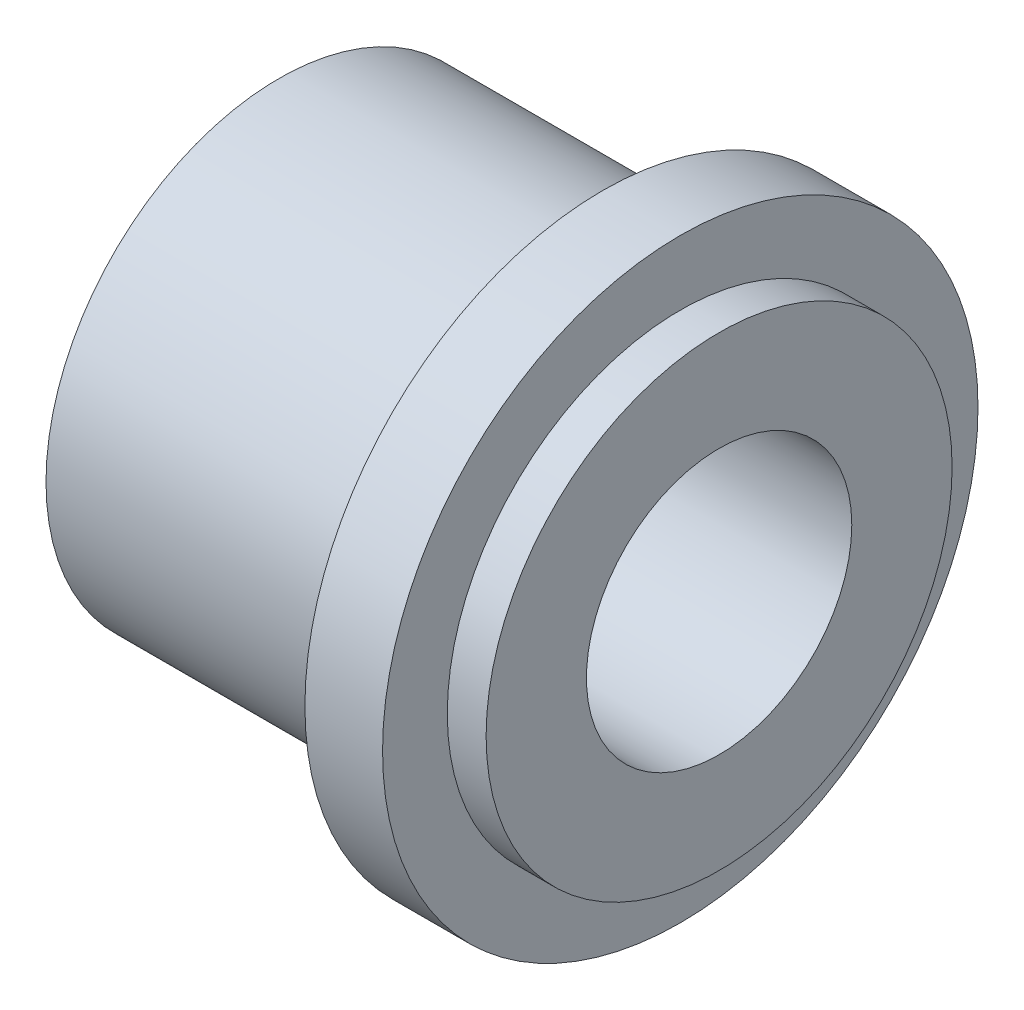
SolidWorks part; units mm, degrees
ref_plane "前视基准面" through (0, 0, 0) normal (0, 0, 1) x (1, 0, 0)
ref_plane "上视基准面" through (0, 0, 0) normal (0, 1, 0) x (1, 0, 0)
ref_plane "右视基准面" through (0, 0, 0) normal (1, 0, 0) x (0, 0, -1)
other "Configuration Table"
sketch "草图1" plane through (0, 0, 0) normal (1, 0, 0) x (0, 0, -1)
  circle A0 centre (0, 0) radius 23
  dimension "D1" = 46
extrude "凸台-拉伸1" add sketch "草图1" along normal blind 6
sketch "草图2" plane through (0, 0, 0) normal (-1, 0, 0) x (0, 0, 1)
  circle A0 centre (0, 0) radius 18
  dimension "D1" = 36
extrude "凸台-拉伸2" add sketch "草图2" along normal blind 25 and the other way blind 9
sketch "草图3" plane through (9, 0, 0) normal (1, 0, 0) x (0, 0, -1)
  circle A0 centre (0, 0) radius 10.25
  dimension "D1" = 20.5
extrude "切除-拉伸1" cut sketch "草图3" against normal through all
